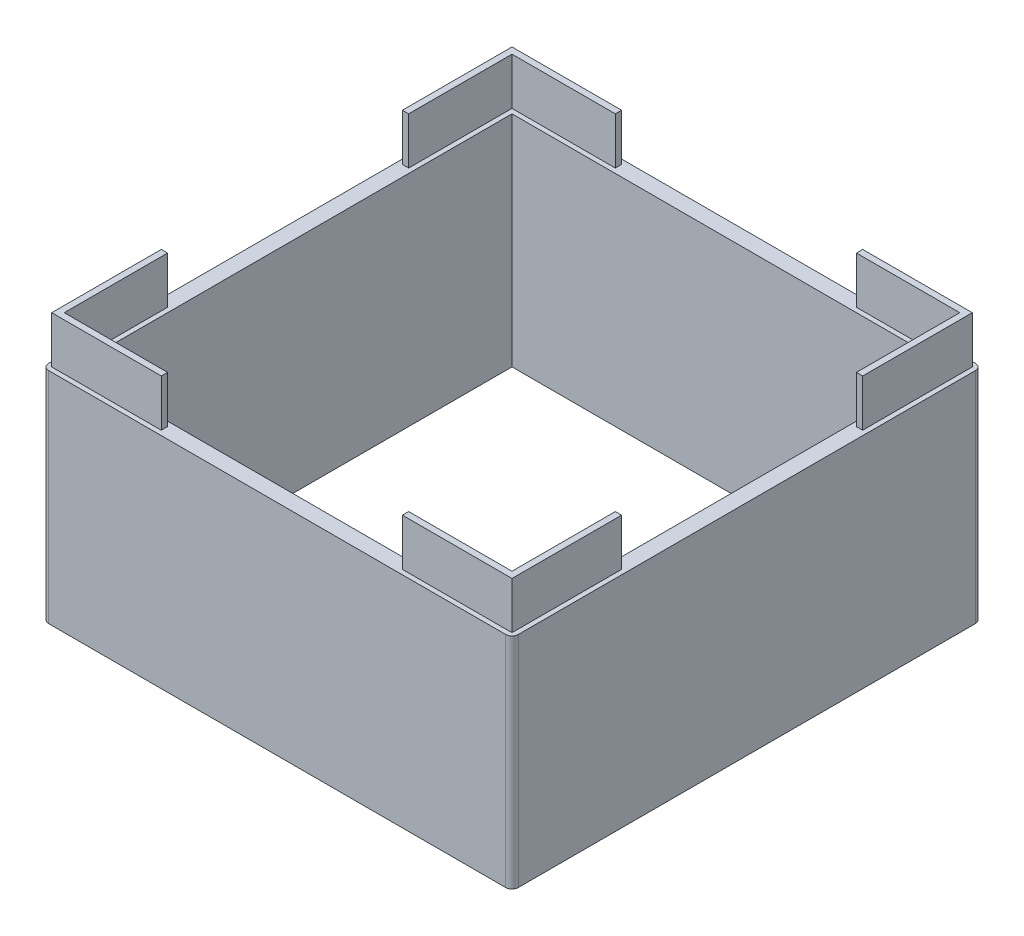
SolidWorks part; units mm, degrees
ref_plane "Front Plane" through (0, 0, 0) normal (0, 0, 1) x (1, 0, 0)
ref_plane "Top Plane" through (0, 0, 0) normal (0, 1, 0) x (1, 0, 0)
ref_plane "Right Plane" through (0, 0, 0) normal (1, 0, 0) x (0, 0, -1)
sketch "Sketch1" plane through (0, 0, 0) normal (0, 1, 0) x (1, 0, 0)
  line L0 (-5, -5) -> (-5, 145)
  line L1 (0, 0) -> (140, 0)
  line L2 (0, 0) -> (0, 140)
  line L3 (0, 140) -> (140, 140)
  line L4 (140, 0) -> (140, 140)
  line L5 (-5, 145) -> (145, 145)
  line L6 (145, -5) -> (145, 145)
  line L7 (-5, -5) -> (145, -5)
  dimension "D1" = 140
  dimension "D2" = 5
extrude "Boss-Extrude1" add sketch "Sketch1" along normal blind 70
sketch "Sketch2" plane through (0, 70, 0) normal (0, 1, 0) x (1, 0, 0)
  line L0 (-3.5, 143.5) -> (31.5, 143.5)
  line L1 (31.5, 143.5) -> (31.5, 141.5)
  line L2 (31.5, 141.5) -> (-1.5, 141.5)
  line L3 (-1.5, 141.5) -> (-1.5, 108.5)
  line L4 (-1.5, 108.5) -> (-3.5, 108.5)
  line L5 (-3.5, 108.5) -> (-3.5, 143.5)
  line L6 (145, 145) -> (-5, 145) construction
  line L7 (140, 140) -> (0, 140) construction
  line L8 (-3.5, 143.5) -> (31.5, 143.5)
  line L9 (145, -5) -> (145, 145) construction
  line L10 (140, 0) -> (140, 140) construction
  line L11 (143.5, 108.5) -> (143.5, 143.5)
  line L12 (141.5, 108.5) -> (143.5, 108.5)
  line L13 (141.5, 141.5) -> (141.5, 108.5)
  line L14 (108.5, 141.5) -> (141.5, 141.5)
  line L15 (108.5, 143.5) -> (108.5, 141.5)
  line L16 (143.5, 143.5) -> (108.5, 143.5)
  line L18 (-5, 145) -> (-5, -5) construction
  line L20 (31.5, 143.5) -> (31.5, 141.5)
  line L21 (31.5, 141.5) -> (-1.5, 141.5)
  line L22 (-1.5, 141.5) -> (-1.5, 108.5)
  line L23 (-1.5, 108.5) -> (-3.5, 108.5)
  line L24 (-3.5, 108.5) -> (-3.5, 143.5)
  line L25 (143.5, 108.5) -> (143.5, 143.5)
  line L26 (141.5, 108.5) -> (143.5, 108.5)
  line L27 (141.5, 141.5) -> (141.5, 108.5)
  line L28 (108.5, 141.5) -> (141.5, 141.5)
  line L29 (108.5, 143.5) -> (108.5, 141.5)
  line L30 (143.5, 143.5) -> (108.5, 143.5)
  line L31 (143.5, -3.5) -> (108.5, -3.5)
  line L32 (108.5, -3.5) -> (108.5, -1.5)
  line L33 (108.5, -1.5) -> (141.5, -1.5)
  line L34 (141.5, -1.5) -> (141.5, 31.5)
  line L35 (141.5, 31.5) -> (143.5, 31.5)
  line L36 (143.5, 31.5) -> (143.5, -3.5)
  line L37 (-3.5, 31.5) -> (-3.5, -3.5)
  line L38 (-1.5, 31.5) -> (-3.5, 31.5)
  line L39 (-1.5, -1.5) -> (-1.5, 31.5)
  line L40 (31.5, -1.5) -> (-1.5, -1.5)
  line L41 (31.5, -3.5) -> (31.5, -1.5)
  line L42 (143.5, -3.5) -> (108.5, -3.5)
  line L43 (108.5, -3.5) -> (108.5, -1.5)
  line L44 (108.5, -1.5) -> (141.5, -1.5)
  line L45 (141.5, -1.5) -> (141.5, 31.5)
  line L46 (141.5, 31.5) -> (143.5, 31.5)
  line L47 (143.5, 31.5) -> (143.5, -3.5)
  line L48 (-3.5, -3.5) -> (31.5, -3.5)
  line L49 (-3.5, 31.5) -> (-3.5, -3.5)
  line L50 (-1.5, 31.5) -> (-3.5, 31.5)
  line L51 (-1.5, -1.5) -> (-1.5, 31.5)
  line L52 (31.5, -1.5) -> (-1.5, -1.5)
  line L53 (31.5, -3.5) -> (31.5, -1.5)
  line L54 (-3.5, -3.5) -> (31.5, -3.5)
  dimension "D1" = 2
  dimension "D2" = 2
  dimension "D3" = 1.5
  dimension "D4" = 1.5
  dimension "D5" = 35
  dimension "D6" = 35
  dimension "D7" = 180
  dimension "D8" = 1.5
  dimension "D9" = 1.5
  dimension "D10" = 1.5
  dimension "D11" = 35
  dimension "D12" = 35
  dimension "D13" = 1.5
  dimension "D14" = 2
  dimension "D15" = 35
  dimension "D16" = 35
extrude "Boss-Extrude2" add sketch "Sketch2" along normal blind 15 contours L5 L4 L3 L2 L1 L0 | L11 L16 L15 L14 L13 L12 | L36 L35 L34 L33 L32 L31 | L37 L48 L41 L40 L39 L38
sketch "Sketch3" plane through (0, 0, 0) normal (0, -1, 0) x (1, 0, 0)
  line L0 (-3.65, 3.65) -> (31.55, 3.65)
  line L1 (31.55, 3.65) -> (31.55, 1.35)
  line L2 (31.55, 1.35) -> (-1.35, 1.35)
  line L3 (-1.35, 1.35) -> (-1.35, -31.55)
  line L4 (-1.35, -31.55) -> (-3.65, -31.55)
  line L5 (-3.65, -31.55) -> (-3.65, 3.65)
  line L6 (-5, -145) -> (-5, 5) construction
  line L7 (0, 0) -> (140, 0) construction
  line L8 (70, 5) -> (70, -145) construction
  line L9 (-5, 5) -> (145, 5) construction
  line L10 (145, -145) -> (-5, -145) construction
  line L11 (-5, -70) -> (145, -70) construction
  line L12 (145, 5) -> (145, -145) construction
  line L13 (143.65, -31.55) -> (143.65, 3.65)
  line L14 (141.35, -31.55) -> (143.65, -31.55)
  line L15 (141.35, 1.35) -> (141.35, -31.55)
  line L16 (108.45, 1.35) -> (141.35, 1.35)
  line L17 (108.45, 3.65) -> (108.45, 1.35)
  line L18 (143.65, 3.65) -> (108.45, 3.65)
  line L19 (143.65, -143.65) -> (108.45, -143.65)
  line L20 (108.45, -143.65) -> (108.45, -141.35)
  line L21 (108.45, -141.35) -> (141.35, -141.35)
  line L22 (141.35, -141.35) -> (141.35, -108.45)
  line L23 (141.35, -108.45) -> (143.65, -108.45)
  line L24 (143.65, -108.45) -> (143.65, -143.65)
  line L25 (-3.65, -108.45) -> (-3.65, -143.65)
  line L26 (-1.35, -108.45) -> (-3.65, -108.45)
  line L27 (-1.35, -141.35) -> (-1.35, -108.45)
  line L28 (31.55, -141.35) -> (-1.35, -141.35)
  line L29 (31.55, -143.65) -> (31.55, -141.35)
  line L30 (-3.65, -143.65) -> (31.55, -143.65)
  dimension "D1" = 2.3
  dimension "D2" = 2.3
  dimension "D3" = 1.35
  dimension "D4" = 1.35
  dimension "D5" = 35.2
  dimension "D6" = 35.2
extrude "Cut-Extrude1" cut sketch "Sketch3" against normal blind 25
fillet "Fillet1" radius 2 4 edges at (145, 35, 5) (-5, 35, 5) (145, 35, -145) (-5, 35, -145)
